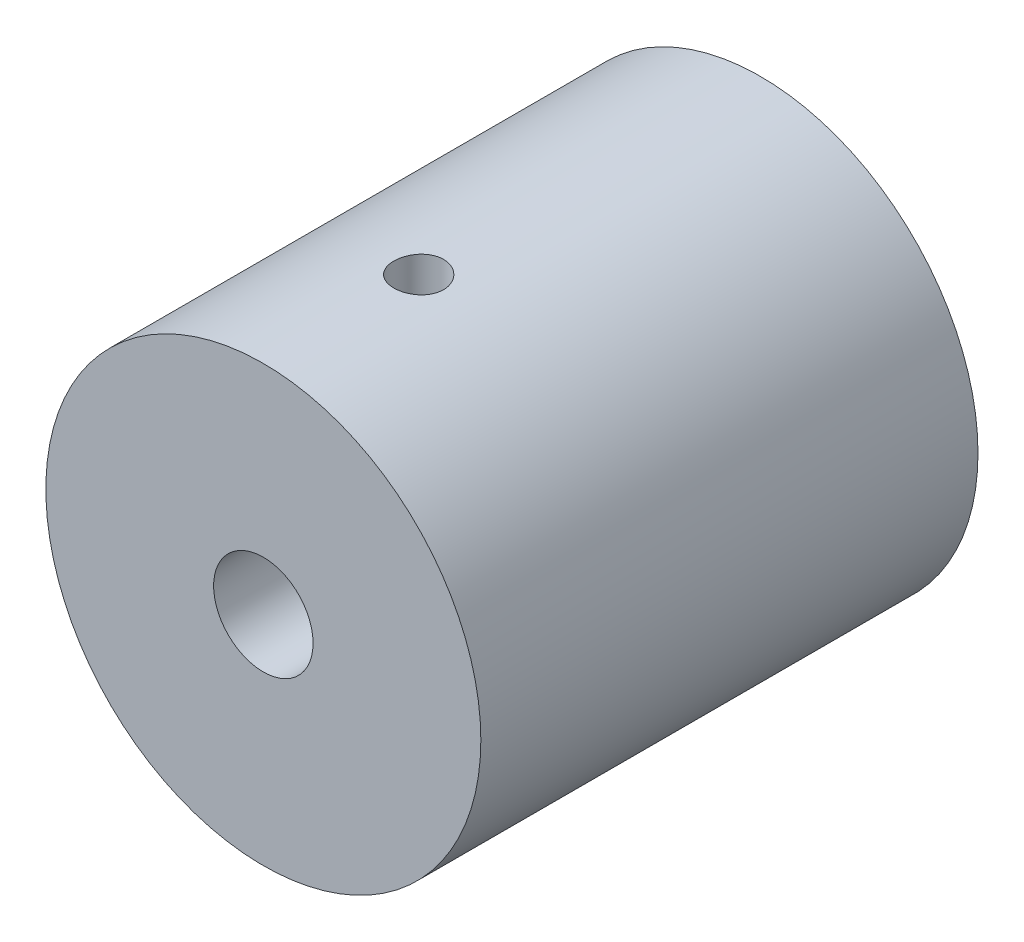
SolidWorks part; units mm, degrees
ref_plane "Alzado" through (0, 0, 0) normal (0, 0, 1) x (1, 0, 0)
ref_plane "Planta" through (0, 0, 0) normal (0, 1, 0) x (1, 0, 0)
ref_plane "Vista lateral" through (0, 0, 0) normal (1, 0, 0) x (0, 0, -1)
sketch "Croquis1" plane through (0, 0, 0) normal (0, 0, 1) x (1, 0, 0)
  circle A0 centre (0, 0) radius 13
  circle A1 centre (0, 0) radius 17.5
  dimension "D1" = 26
  dimension "D2" = 35
extrude "Saliente-Extruir1" add sketch "Croquis1" along normal blind 10
sketch "Croquis2" plane through (0, 0, 10) normal (0, 0, 1) x (1, 0, 0)
  circle A0 centre (0, 0) radius 17.5
extrude "Saliente-Extruir2" add sketch "Croquis2" along normal blind 30
sketch "Croquis4" plane through (0, 0, 0) normal (1, 0, 0) x (0, 0, -1)
  line L0 (-10, 0) -> (-10, 13)
  line L1 (-10, 13) -> (-15, 0)
  line L2 (-15, 0) -> (-10, 0)
  line L3 (0, -17.5) -> (0, 17.5) construction
  dimension "D1" = 5
  dimension "D2" = 13
  dimension "D3" = 10
ref_axis "Eje3" through (0, 0, 40) along (0, 0, -1)
revolve "Cortar-Revolución1" cut sketch "Croquis4" angle 360 about axis through (0, 0, 40) along (0, 0, -1)
sketch "Croquis12" plane through (0, 0, 40) normal (0, 0, 1) x (1, 0, 0)
  circle A0 centre (0, 0) radius 4
  dimension "D1" = 8
extrude "Cortar-Extruir1" cut sketch "Croquis12" against normal through all
sketch "Croquis13" plane through (0, 0, 0) normal (0, 0, -1) x (-1, 0, 0)
  circle A3 centre (-15.25, 0) radius 1
  circle A4 centre (15.25, 0) radius 1
  dimension "D1" = 2
  dimension "D2" = 2
extrude "Cortar-Extruir2" cut sketch "Croquis13" against normal blind 10
sketch "Croquis14" plane through (0, 0, 0) normal (0, 1, 0) x (1, 0, 0)
  circle A0 centre (0, -27.5) radius 2
  dimension "D2" = 4
extrude "Cortar-Extruir3" cut sketch "Croquis14" along normal through all
